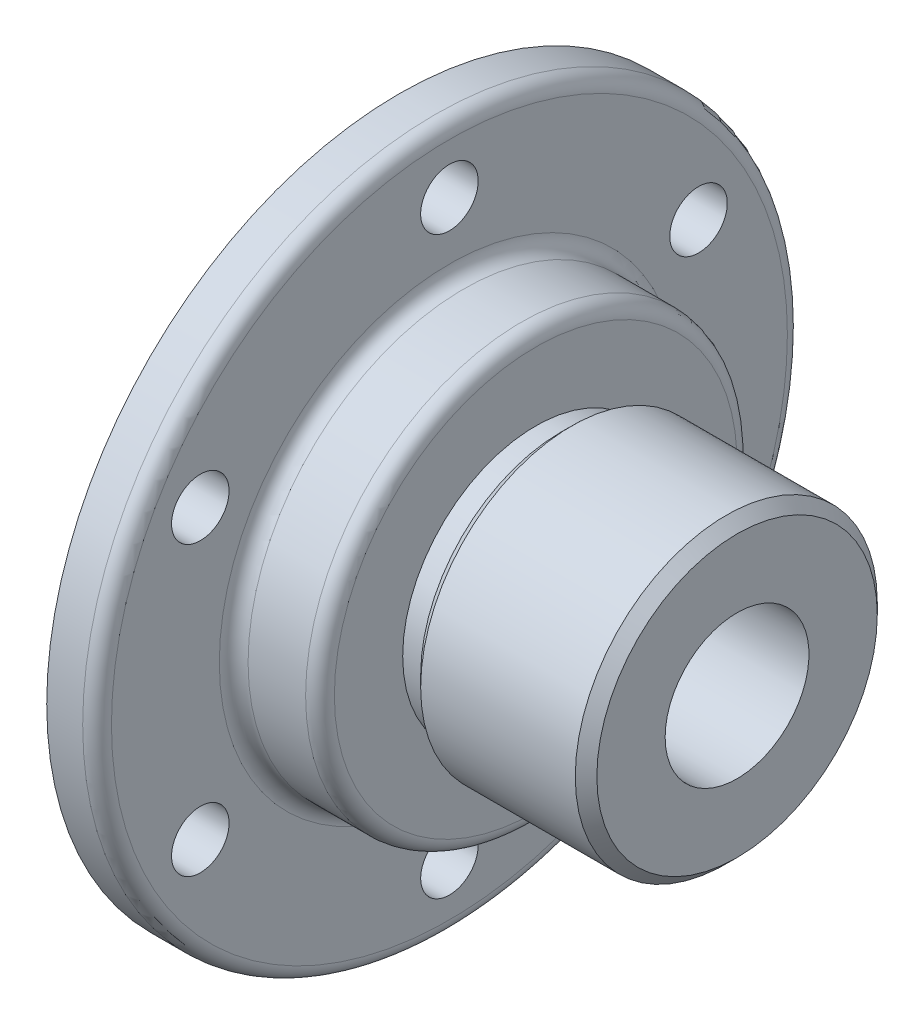
SolidWorks part; units mm, degrees
ref_plane "前基準面" through (0, 0, 0) normal (0, 0, 1) x (1, 0, 0)
ref_plane "上基準面" through (0, 0, 0) normal (0, 1, 0) x (1, 0, 0)
ref_plane "右基準面" through (0, 0, 0) normal (1, 0, 0) x (0, 0, -1)
sketch "草圖1" plane through (0, 0, 0) normal (0, 0, 1) x (1, 0, 0)
  line L0 (0, 0) -> (71.1482, 0) construction
  line L1 (0, 0) -> (0, 49)
  line L2 (0, 49) -> (7, 49)
  line L3 (7, 49) -> (7, 30)
  line L4 (7, 30) -> (19, 30)
  line L5 (19, 30) -> (19, 18.5)
  line L6 (19, 18.5) -> (22.5, 18.5)
  line L7 (22.5, 18.5) -> (22.5, 21)
  line L8 (22.5, 21) -> (47, 21)
  line L9 (47, 21) -> (47, 0)
  line L10 (0, 0) -> (47, 0)
  dimension "D1" = 42
  dimension "D2" = 37
  dimension "D3" = 60
  dimension "D4" = 98
  dimension "D5" = 7
  dimension "D6" = 3.5
  dimension "D7" = 28
  dimension "D8" = 47
revolve "旋轉1" add sketch "草圖1" angle 360 about L0
cosmetic thread "裝飾螺紋線1" parameters "D2"=37
sketch "草圖2" plane through (0, 0, 0) normal (0, 0, 1) x (1, 0, 0)
  line L0 (0, 0) -> (56.1868, 0) construction
  line L1 (47, 0) -> (47, 10)
  line L2 (47, -21) -> (47, 21) construction
  line L3 (47, 10) -> (10, 10)
  line L4 (10, 10) -> (10, 22.5)
  line L5 (10, 22.5) -> (0, 22.5)
  line L6 (0, 49) -> (0, -49) construction
  line L7 (0, 22.5) -> (0, 0)
  line L8 (0, 0) -> (47, 0)
  dimension "D1" = 20
  dimension "D2" = 45
  dimension "D3" = 10
revolve "除料-旋轉1" cut sketch "草圖2" angle 360 about L0
chamfer "導角1" distance 1.5 angle 45 2 edges at (22.5, 0, 21) (47, 0, 21)
sketch "草圖3" plane through (7, 0, 0) normal (1, 0, 0) x (0, 0, -1)
  line L0 (0, 0) -> (0, 40) construction
  circle A0 centre (0, 0) radius 40 construction
  circle A2 centre (0, 40) radius 4
  dimension "D1" = 80
  dimension "D2" = 8
extrude "伸長1" cut sketch "草圖3" against normal through all
pattern_circular "環狀複製排列1" count 6 over 360 about axis through (0, 0, 0) along (1, 0, 0) of "伸長1"
fillet "圓角1" radius 2 3 edges at (19, 0, 30) (7, 0, 30) (7, 0, 49)
